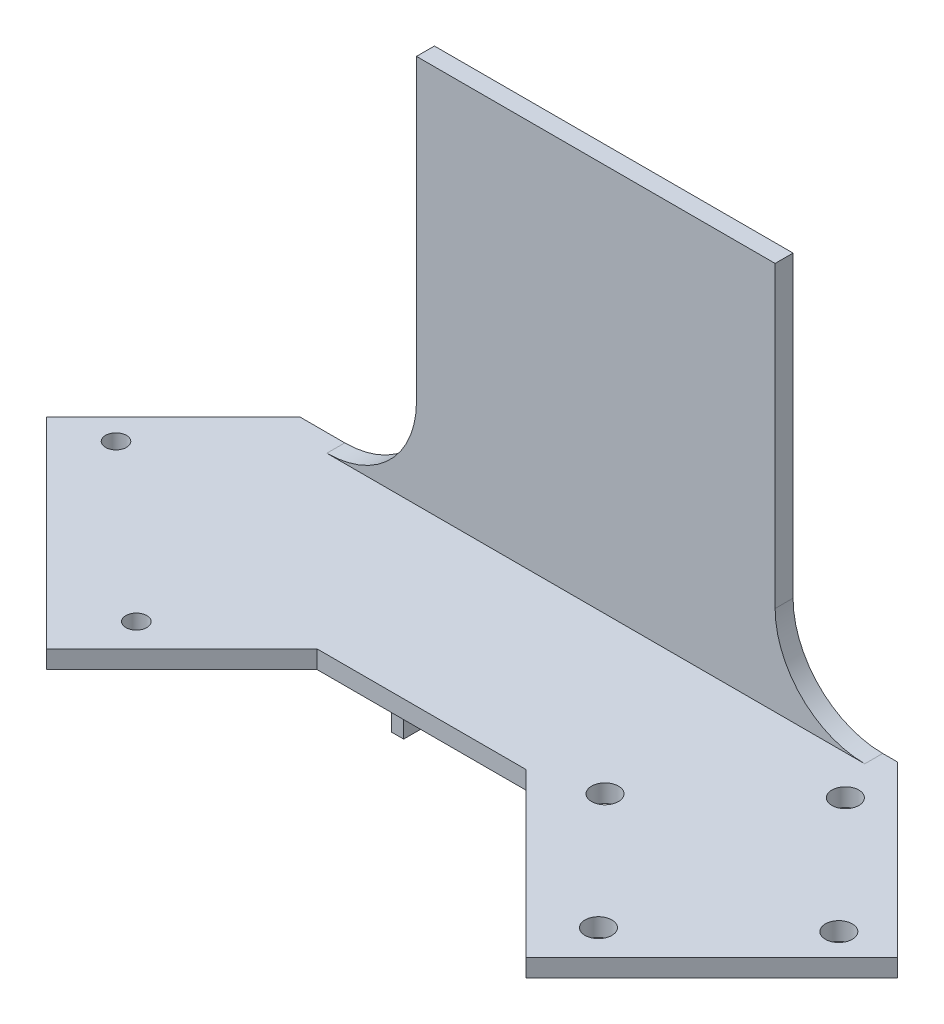
SolidWorks part; units mm, degrees
ref_plane "Front Plane" through (0, 0, 0) normal (0, 0, 1) x (1, 0, 0)
ref_plane "Top Plane" through (0, 0, 0) normal (0, 1, 0) x (1, 0, 0)
ref_plane "Right Plane" through (0, 0, 0) normal (1, 0, 0) x (0, 0, -1)
sketch "Sketch1" plane through (0, 0, 0) normal (0, 1, 0) x (1, 0, 0)
  line L0 (-24.1815, 0) -> (30.7185, 0) construction
  line L2 (-17.65, -1) -> (17.65, -1)
  line L3 (-19.65, -1) -> (-19.65, 1)
  line L4 (-19.65, 1) -> (19.65, 1)
  line L5 (19.65, -1) -> (19.65, 1)
  line L6 (0, 0) -> (19.65, 1) construction
  line L7 (-19.65, 1) -> (0, 0) construction
  line L9 (-19.65, -1) -> (-19.65, -14)
  line L10 (-19.65, -14) -> (-17.65, -14)
  line L11 (-17.65, -1) -> (-17.65, -14)
  line L13 (19.65, -1) -> (19.65, -14)
  line L14 (19.65, -14) -> (17.65, -14)
  line L15 (17.65, -1) -> (17.65, -14)
  point P3 (0, 0)
  dimension "D1" = 39.3
  dimension "D2" = 2
  dimension "D3" = 15
  dimension "D4" = 15
  dimension "D5" = 2
  dimension "D6" = 2
extrude "Boss-Extrude1" add sketch "Sketch1" along normal blind 20
sketch "Sketch2" plane through (0, 20, 0) normal (0, 1, 0) x (1, 0, 0)
  line L0 (-32.6208, 1) -> (36.7708, 1) construction
  line L1 (-50, 1) -> (50, 1)
  line L2 (50, 1) -> (78.2843, -27.2843)
  line L3 (78.2843, -27.2843) -> (47.2021, -58.3665)
  line L4 (47.2021, -58.3665) -> (20, -31.1644)
  line L5 (20, -31.1644) -> (-15, -31.1644)
  line L6 (-15, -31.1644) -> (-37.631, -53.7954)
  line L8 (-71.2132, -20.2132) -> (-50, 1)
  line L9 (0, 89.4519) -> (0, -66.1008) construction
  line L15 (-71.2132, -20.2132) -> (-37.631, -53.7954)
  line L16 (0, 24.5) -> (63.1967, -42.3718) construction
  line L17 (29.93, -47.1331) -> (71.6384, -7.7168) construction
  circle A0 centre (0, 24.5) radius 75 construction
  circle A1 centre (0, 24.5) radius 87.5 construction
  circle A2 centre (-61.8501, -17.9212) radius 1.75
  circle A3 centre (-34.0425, -42.3289) radius 1.75
  circle A4 centre (48.9623, -48.0185) radius 2.25
  circle A6 centre (69.6382, -28.4789) radius 2.25
  circle A7 centre (50.7965, -8.5415) radius 2.25
  circle A8 centre (30.1206, -28.0811) radius 2.25
  point P16 (0, 24.5)
  dimension "D10" = 150
  dimension "D13" = 175
  dimension "D14" = 37
  dimension "D16" = 3.5
  dimension "D17" = 3.5
  dimension "D19" = 4.5
  dimension "D1" = 50
  dimension "D2" = 50
  dimension "D3" = 30
  dimension "D4" = 40
  dimension "D5" = 23.5
  dimension "D6" = 135
  dimension "D7" = 15
  dimension "D8" = 20
  dimension "D9" = 135
  dimension "D11" = 135
  dimension "D12" = 135
  dimension "D15" = 5
  dimension "D18" = 28.448
  dimension "D20" = 13.716
extrude "Boss-Extrude2" add sketch "Sketch2" along normal blind 3
fillet "Fillet1" radius 8 3 edges at (17.65, 20, 7.5) (0, 20, 1) (-17.65, 20, 7.5)
sketch "Sketch3" plane through (0, 23, 0) normal (0, 1, 0) x (1, 0, 0)
  line L0 (2.5, -31.1644) -> (2.5, 26.1972) construction
  line L1 (-15, -31.1644) -> (20, -31.1644) construction
  line L2 (50, 1) -> (-50, 1) construction
  line L3 (-27.5, -2) -> (32.5, -2)
  line L4 (-27.5, -2) -> (-27.5, 1)
  line L5 (-27.5, 1) -> (32.5, 1)
  line L6 (32.5, -2) -> (32.5, 1)
  line L7 (-27.5, -2) -> (32.5, 1) construction
  line L8 (-27.5, 1) -> (32.5, -2) construction
  point P4 (2.5, -0.5)
  dimension "D1" = 3
  dimension "D2" = 60
extrude "Boss-Extrude3" add sketch "Sketch3" along normal blind 65
fillet "Fillet2" radius 15 2 edges at (32.5, 23, 0.5) (-27.5, 23, 0.5)
